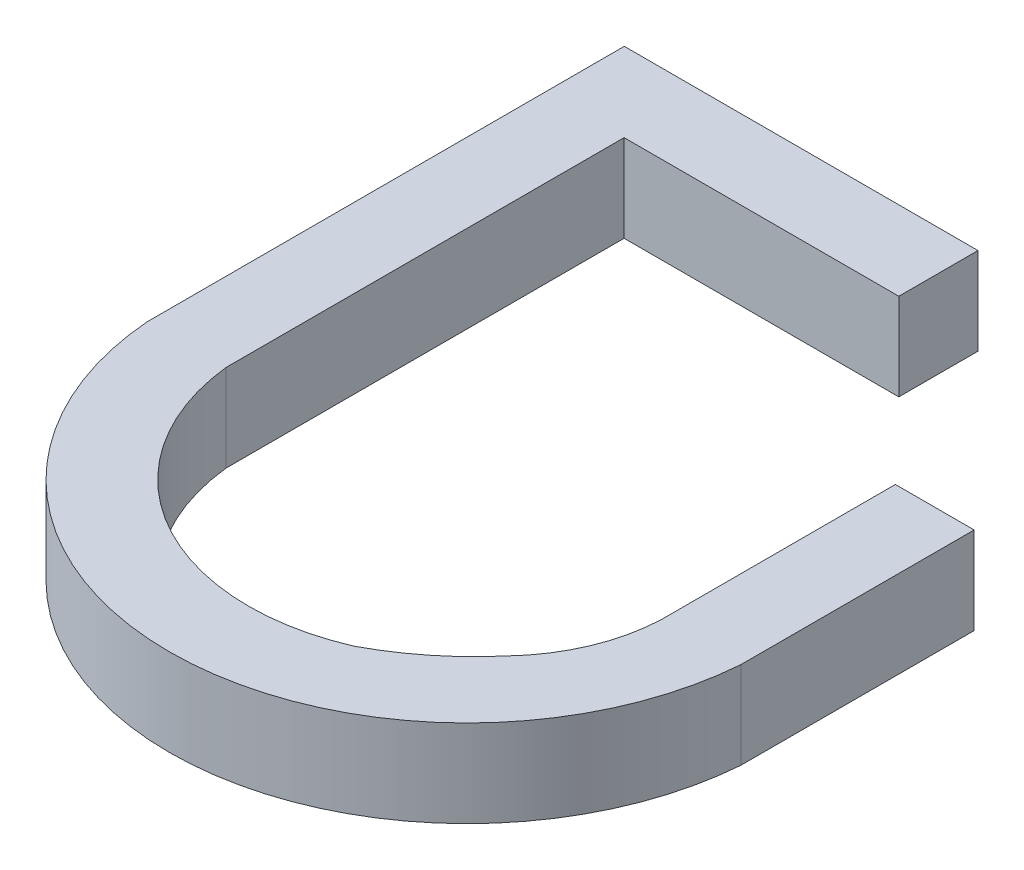
SolidWorks part; units mm, degrees
ref_plane "Front Plane" through (0, 0, 0) normal (0, 0, 1) x (1, 0, 0)
ref_plane "Top Plane" through (0, 0, 0) normal (0, 1, 0) x (1, 0, 0)
ref_plane "Right Plane" through (0, 0, 0) normal (1, 0, 0) x (0, 0, -1)
sketch "Sketch1" plane through (0, 0, 0) normal (0, 1, 0) x (1, 0, 0)
  line L0 (29, 109.5) -> (145, 109.5) construction
  line L1 (0, 0) -> (0, 116.767) construction
  line L2 (23.0118, 80.0276) -> (150.0261, 80.0276) construction
  line L3 (0, 80.0276) -> (0, 219.0676)
  line L4 (0, 219.0676) -> (103.0401, 219.0676)
  line L5 (103.0401, 219.0676) -> (103.0401, 195.9995)
  line L6 (103.0401, 195.9995) -> (23.0118, 195.9995)
  line L7 (23.0118, 195.9995) -> (23.0118, 161.0132)
  line L8 (150.0261, 80.0276) -> (150.0261, 148.0117)
  line L9 (150.0261, 148.0117) -> (172.9743, 148.0117)
  line L10 (172.9743, 80.0276) -> (172.9743, 148.0117)
  line L11 (172.9743, 80.0276) -> (175.6962, 80.0276) construction
  line L12 (103.0401, 219.0676) -> (173.9279, 219.0676) construction
  line L13 (23.0118, 136.0582) -> (23.0118, 80.0276)
  line L14 (173.9279, 219.0676) -> (173.9279, 172.1301) construction
  line L16 (173.9279, 172.1301) -> (150.0261, 172.1301)
  line L17 (173.9279, 172.1301) -> (173.9279, 219.0676)
  line L18 (173.9279, 219.0676) -> (127.0177, 219.0676)
  line L19 (127.0177, 195.9995) -> (127.0177, 219.0676)
  line L22 (127.0177, 195.9995) -> (150.0261, 195.9995)
  line L23 (150.0261, 172.1301) -> (150.0261, 195.9995)
  arc A0 (0, 80.0276) -> (172.9743, 80.0276) centre (86.4872, 86.7884) ccw
  arc A1 (23.0118, 80.0276) -> (112.0664, 28.4105) centre (86.519, 86.9649) ccw
  arc A2 (23.0118, 161.0132) -> (136.7449, 48.2112) centre (18.9852, 43.2164) cw
  arc A3 (23.0118, 136.0582) -> (112.0664, 28.4105) centre (17.0299, 40.4491) cw
  arc A4 (136.7449, 48.2112) -> (150.0261, 80.0276) centre (101.1223, 81.7615) ccw
extrude "Boss-Extrude1" add sketch "Sketch1" along normal blind 25.4
sketch "Sketch2" plane through (0, 25.4, 0) normal (0, 1, 0) x (1, 0, 0)
  line L1 (127.0177, 219.0676) -> (173.9279, 219.0676)
  line L2 (127.0177, 219.0676) -> (127.0177, 172.1301)
  line L3 (127.0177, 172.1301) -> (173.9279, 172.1301)
  line L4 (173.9279, 219.0676) -> (173.9279, 172.1301)
extrude "Cut-Extrude1" cut sketch "Sketch2" against normal through all both and the other way through all
sketch "Sketch3" plane through (0, 25.4, 0) normal (0, 1, 0) x (1, 0, 0)
  line L0 (23.0118, 161.0132) -> (23.0118, 136.0582)
  arc A0 (112.0664, 28.4105) -> (136.7449, 48.2112) centre (72.7035, 102.7496) ccw
  arc A1 (23.0118, 161.0132) -> (136.7449, 48.2112) centre (18.9852, 43.2164) cw
  arc A2 (112.0664, 28.4105) -> (23.0118, 136.0582) centre (17.0299, 40.4491) ccw
extrude "Cut-Extrude2" cut sketch "Sketch3" against normal through all both and the other way through all
